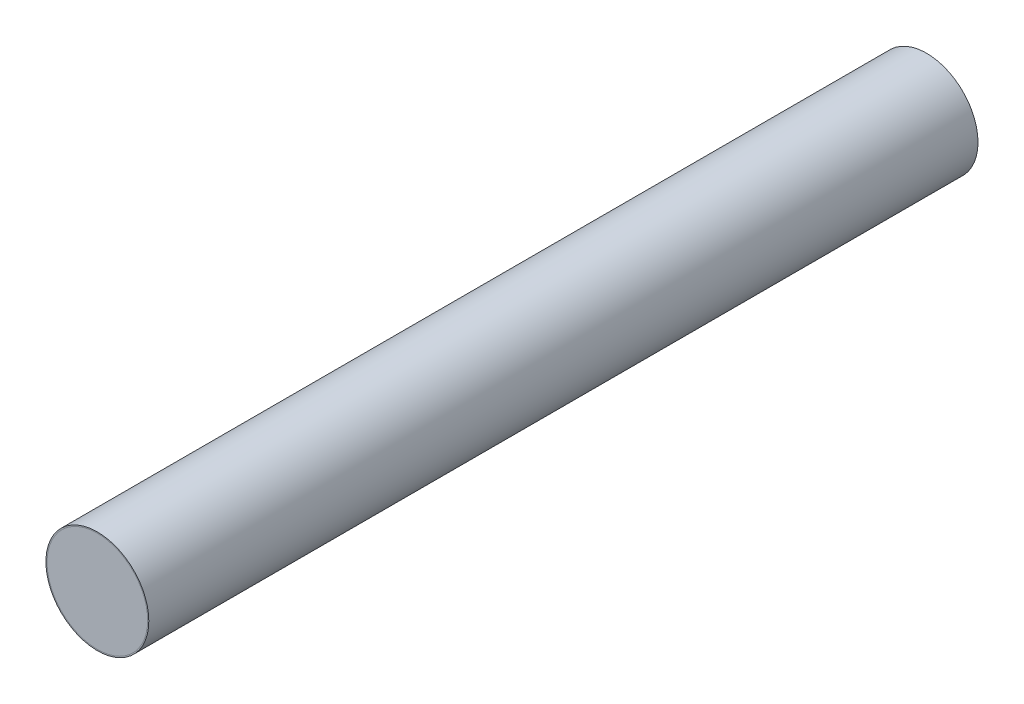
SolidWorks part; units mm, degrees
other "8223AL"
other "03170L"
material "APCP"
ref_plane "Front Plane" through (0, 0, 0) normal (0, 0, 1) x (1, 0, 0)
ref_plane "Top Plane" through (0, 0, 0) normal (0, 1, 0) x (1, 0, 0)
ref_plane "Right Plane" through (0, 0, 0) normal (1, 0, 0) x (0, 0, -1)
sketch "Sketch1" plane through (0, 0, 0) normal (0, 0, 1) x (1, 0, 0)
  circle A0 centre (0, 0) radius 16.5481
  circle A1 centre (0, 0) radius 16.1798
  dimension "D1" = 33.0962
  dimension "D2" = 32.3596
extrude "Boss-Extrude1" add sketch "Sketch1" along normal blind 266.7
sketch "Sketch2" plane through (0, 0, 0) normal (0, 0, 1) x (1, 0, 0)
  circle A0 centre (0, 0) radius 16.1798
  circle A1 centre (0, 0) radius 16.1798 construction
extrude "Boss-Extrude2" add sketch "Sketch2" along normal up to surface (266.7 mm away) separate body up to face at (16.5481, 0, 266.7)
sketch "Sketch3" [suppressed] plane through (0, 0, 72.5424) normal (0, 0, 1) x (1, 0, 0)
  point P0 (0, 0)
hole_wizard "7/16 (0.438) Diameter Hole1" [suppressed] positions "Sketch3" profile "Sketch4" hole size "7/16" standard "ANSI Inch"
sketch "Sketch4" plane through (0, 0, 72.5424) normal (1, 0, 0) x (0, -1, 0)
  line L0 (0, 0) -> (0, 72.5424)
  line L1 (0, 72.5424) -> (5.5626, 72.5424)
  line L2 (5.5626, 72.5424) -> (5.5626, 0)
  line L5 (5.5626, 0) -> (0, 0)
  line L11 (0, -6.35) -> (0, 107.95) construction
  dimension "Thru Hole Dia." = 11.1252
  dimension "Thru Hole Depth" = 72.5424
